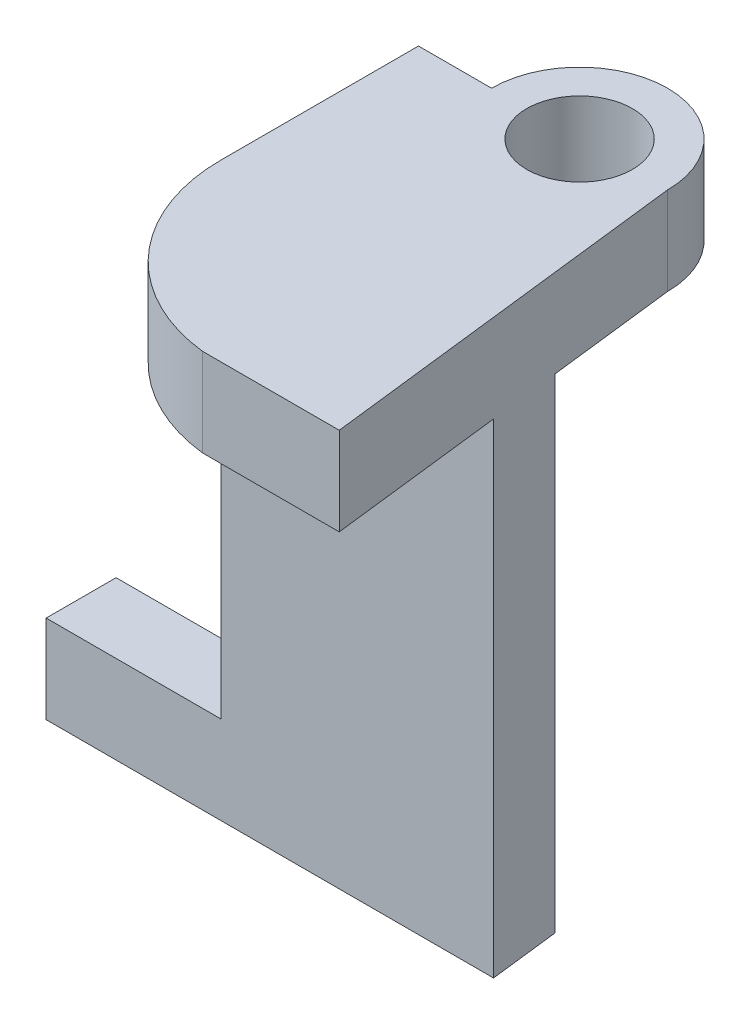
SolidWorks part; units mm, degrees
ref_plane "Alzado" through (0, 0, 0) normal (0, 0, 1) x (1, 0, 0)
ref_plane "Planta" through (0, 0, 0) normal (0, 1, 0) x (1, 0, 0)
ref_plane "Vista lateral" through (0, 0, 0) normal (1, 0, 0) x (0, 0, -1)
sketch "Croquis2" plane through (0, 0, 0) normal (0, 1, 0) x (1, 0, 0)
  line L1 (7.5, -21.15) -> (5, 0)
  line L3 (-5, 0) -> (-9.15, 0)
  line L4 (-9.15, 0) -> (-9.15, -11.2124)
  line L5 (7.5, -21.15) -> (-0.1272, -21.15)
  line L6 (-0.1272, -21.15) -> (-0.265, -21.15)
  circle A0 centre (0, 0) radius 3
  arc A1 (5, 0) -> (-5, 0) centre (0, 0) ccw
  arc A2 (-9.15, -11.2124) -> (-0.265, -21.15) centre (0.85, -11.2124) ccw
  dimension "D1" = 6
  dimension "D2" = 10
  dimension "D5" = 20
  dimension "D3" = 21.15
  dimension "D4" = 7.5
  dimension "D6" = 4.15
extrude "Saliente-Extruir1" add sketch "Croquis2" along normal blind 5
sketch "Croquis3" plane through (0, 0, 0) normal (0, -1, 0) x (1, 0, 0)
  line L0 (7.5, 21.15) -> (5, 0) construction
  line L1 (-9.15, 11.2124) -> (6.3253, 11.2124)
  line L2 (-9.15, 11.2124) -> (-9.15, 7.24)
  line L3 (-9.15, 7.24) -> (5.8558, 7.24)
  line L5 (5.8558, 7.24) -> (6.3253, 11.2124)
  dimension "D1" = 4
extrude "Saliente-Extruir2" add sketch "Croquis3" along normal blind 22.5
sketch "Croquis4" plane through (0, -22.5, 0) normal (0, -1, 0) x (1, 0, 0)
  line L0 (5.8558, 7.24) -> (6.3253, 11.2124)
  line L1 (6.3253, 11.2124) -> (-19.0852, 11.2124)
  line L3 (5.8558, 7.24) -> (-19.0852, 7.24)
  line L4 (-19.0852, 11.2124) -> (-19.0852, 7.24)
extrude "Saliente-Extruir3" add sketch "Croquis4" along normal blind 5
